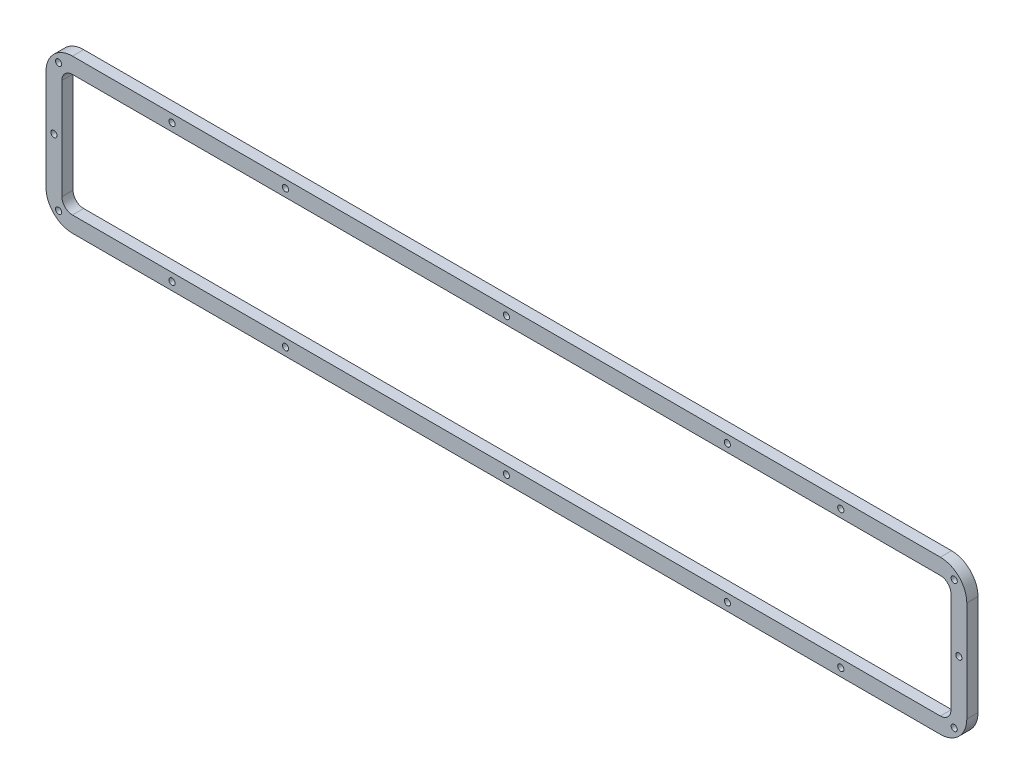
SolidWorks part; units mm, degrees
ref_plane "Front Plane" through (0, 0, 0) normal (0, 0, 1) x (1, 0, 0)
ref_plane "Top Plane" through (0, 0, 0) normal (0, 1, 0) x (1, 0, 0)
ref_plane "Right Plane" through (0, 0, 0) normal (1, 0, 0) x (0, 0, -1)
sketch "Sketch1" plane through (0, 0, 0) normal (0, 0, 1) x (1, 0, 0)
  circle A0 centre (0, 0) radius 5
  dimension "D1" = 10
sketch "Sketch2" plane through (0, 0, 0) normal (0, 0, 1) x (1, 0, 0)
  line L0 (-492, -69) -> (492, -69)
  line L1 (504, -57) -> (504, 57)
  line L2 (492, 69) -> (-492, 69)
  line L3 (-504, 57) -> (-504, -57)
  line L8 (-492, -87) -> (492, -87)
  line L9 (522, -57) -> (522, 57)
  line L10 (492, 87) -> (-492, 87)
  line L11 (-522, 57) -> (-522, -57)
  line L12 (492, 87) -> (-492, 87) construction
  line L13 (-522, 57) -> (-522, -57) construction
  line L14 (-492, -87) -> (492, -87) construction
  line L15 (522, -57) -> (522, 57) construction
  arc A0 (492, -69) -> (504, -57) centre (492, -57) ccw
  arc A1 (504, 57) -> (492, 69) centre (492, 57) ccw
  arc A2 (-492, 69) -> (-504, 57) centre (-492, 57) ccw
  arc A3 (-504, -57) -> (-492, -69) centre (-492, -57) ccw
  arc A8 (492, -87) -> (522, -57) centre (492, -57) ccw
  arc A9 (522, 57) -> (492, 87) centre (492, 57) ccw
  arc A10 (-492, 87) -> (-522, 57) centre (-492, 57) ccw
  arc A11 (-522, -57) -> (-492, -87) centre (-492, -57) ccw
  arc A12 (-492, 87) -> (-522, 57) centre (-492, 57) ccw construction
  arc A13 (-522, -57) -> (-492, -87) centre (-492, -57) ccw construction
  arc A14 (492, -87) -> (522, -57) centre (492, -57) ccw construction
  arc A15 (522, 57) -> (492, 87) centre (492, 57) ccw construction
  dimension "D2" = 18
extrude "Boss-Extrude1" add sketch "Sketch2" along normal blind 12.7
sketch "Sketch4" plane through (0, 0, 12.7) normal (0, 0, 1) x (1, 0, 0)
  circle A0 centre (-507.7279, 72.7279) radius 3.5
  circle A1 centre (-507.7279, -72.7279) radius 3.5
  circle A2 centre (-250.5, -78) radius 3.5
  circle A3 centre (-250.5, 78) radius 3.5
  circle A4 centre (250.5, 78) radius 3.5
  circle A5 centre (250.5, -78) radius 3.5
  circle A6 centre (507.7279, 72.7279) radius 3.5
  circle A7 centre (507.7279, -72.7279) radius 3.5
  circle A8 centre (-507.7279, 72.7279) radius 3.175 construction
  circle A9 centre (-507.7279, -72.7279) radius 3.175 construction
  circle A10 centre (-250.5, -78) radius 3.175 construction
  circle A11 centre (250.5, -78) radius 3.175 construction
  circle A12 centre (507.7279, -72.7279) radius 3.175 construction
  circle A13 centre (507.7279, 72.7279) radius 3.175 construction
  circle A14 centre (250.5, 78) radius 3.175 construction
  circle A15 centre (-250.5, 78) radius 3.175 construction
  dimension "D1" = 7
extrude "Cut-Extrude1" cut sketch "Sketch4" against normal through all
sketch "Sketch5" plane through (0, 0, 12.7) normal (0, 0, 1) x (1, 0, 0)
  line L0 (-507.7279, 72.7279) -> (-250.5, 72.7279) construction
  line L1 (-504, 0) -> (-522, 0) construction
  line L2 (-504, 57) -> (-504, -57) construction
  line L3 (-522, 57) -> (-522, -57) construction
  line L4 (504, 0) -> (522, 0) construction
  line L5 (504, -57) -> (504, 57) construction
  line L6 (522, -57) -> (522, 57) construction
  line L7 (0, 78) -> (0, -78) construction
  line L8 (507.7279, 72.7279) -> (250.5, 72.7279) construction
  circle A0 centre (-379.114, 78) radius 3.5
  circle A1 centre (-513, 0) radius 3.5
  circle A2 centre (-379.114, -78) radius 3.5
  circle A3 centre (0, -78) radius 3.5
  circle A4 centre (0, 78) radius 3.5
  circle A5 centre (379.114, 78) radius 3.5
  circle A6 centre (379.114, -78) radius 3.5
  circle A7 centre (513, 0) radius 3.5
  circle A13 centre (-507.7279, 72.7279) radius 3.5 construction
  circle A14 centre (-507.7279, 72.7279) radius 3.5 construction
  circle A16 centre (-250.5, 78) radius 3.5 construction
  circle A17 centre (-250.5, 78) radius 3.5 construction
  circle A18 centre (-250.5, -78) radius 3.5 construction
  circle A19 centre (-250.5, -78) radius 3.5 construction
  circle A20 centre (250.5, 78) radius 3.5 construction
  circle A21 centre (250.5, 78) radius 3.5 construction
  point P28 (-379.114, 72.7279)
  point P44 (379.114, 72.7279)
extrude "Cut-Extrude2" cut sketch "Sketch5" against normal through all both and the other way through all
